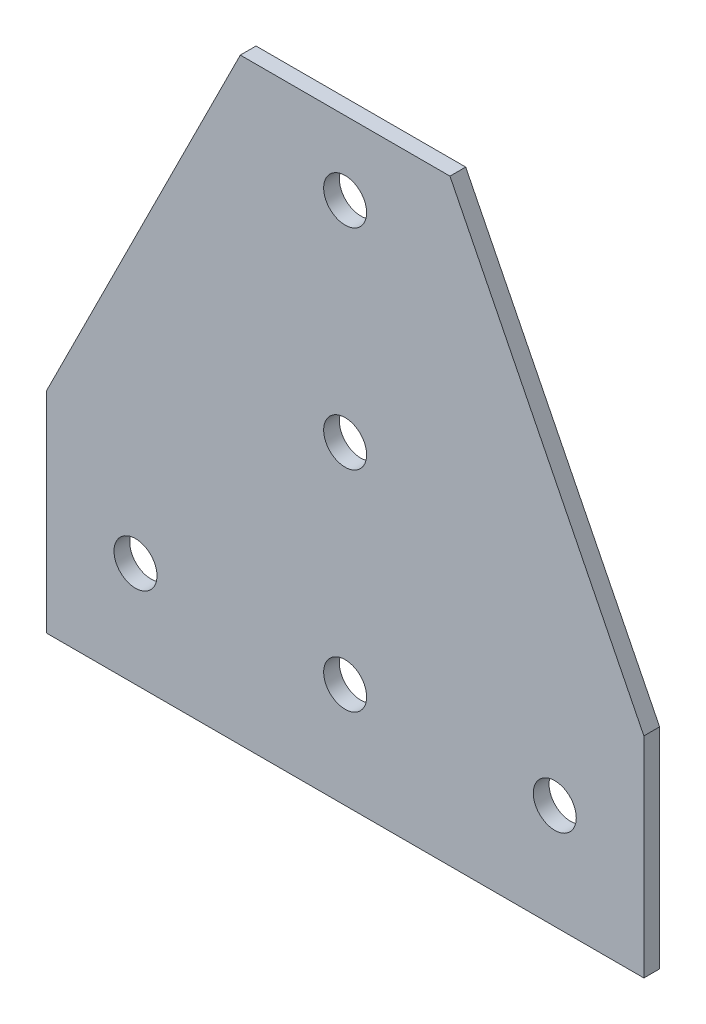
SolidWorks part; units mm, degrees
material "Простая углеродистая сталь"
ref_plane "Спереди" through (0, 0, 0) normal (0, 0, 1) x (1, 0, 0)
ref_plane "Сверху" through (0, 0, 0) normal (0, 1, 0) x (1, 0, 0)
ref_plane "Справа" through (0, 0, 0) normal (1, 0, 0) x (0, 0, -1)
sketch "Эскиз1" plane through (0, 0, 0) normal (0, 0, 1) x (1, 0, 0)
  line L0 (-57, -20) -> (57, -20)
  line L1 (57, -20) -> (57, 20)
  line L2 (57, 20) -> (20, 94)
  line L3 (20, 94) -> (-20, 94)
  line L4 (-20, 94) -> (-57, 20)
  line L5 (-57, 20) -> (-57, -20)
  line L6 (-40, 0) -> (0, 0) construction
  line L7 (0, 0) -> (40, 0) construction
  line L8 (0, 0) -> (0, 40) construction
  line L9 (0, 40) -> (0, 80) construction
  circle A0 centre (0, 0) radius 4.1
  circle A1 centre (-40, 0) radius 4.1
  circle A2 centre (40, 0) radius 4.1
  circle A3 centre (0, 40) radius 4.1
  circle A4 centre (0, 80) radius 4.1
  point P6 (-57, 0)
  point P7 (57, 0)
  point P9 (0, -20)
  point P10 (0, 94)
  dimension "D3" = 8.2
  dimension "D1" = 114
  dimension "D2" = 114
  dimension "D4" = 40
  dimension "D5" = 40
  dimension "D6" = 40
  dimension "D7" = 40
extrude "База" add sketch "Эскиз1" along normal mid plane 3
